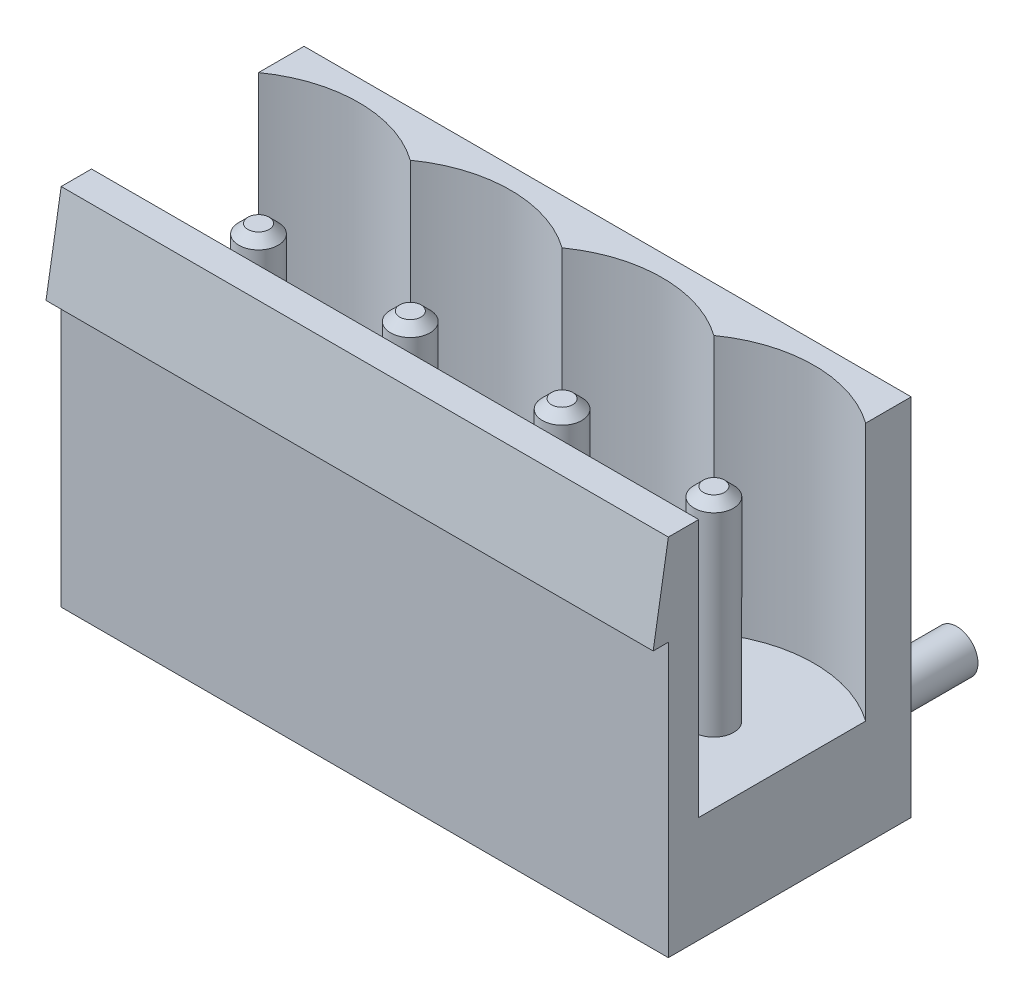
SolidWorks part; units mm, degrees
ref_plane "Спереди" through (0, 0, 0) normal (0, 0, 1) x (1, 0, 0)
ref_plane "Сверху" through (0, 0, 0) normal (0, 1, 0) x (1, 0, 0)
ref_plane "Справа" through (0, 0, 0) normal (1, 0, 0) x (0, 0, -1)
sketch "Эскиз1" plane through (0, 0, 0) normal (1, 0, 0) x (0, -1, 0)
  line L0 (-9, 0) -> (-9, -0.5)
  line L1 (0, 0) -> (-9, 0)
  line L2 (0, 0) -> (0, 8)
  line L3 (0, 8) -> (-12, 8)
  line L4 (-12, 0) -> (-12, 8)
  line L5 (-9, -0.5) -> (-12, 0)
  dimension "D1" = 12
  dimension "D2" = 8
  dimension "D3" = 3
  dimension "D4" = 0.5
extrude "Вытянуть1" add sketch "Эскиз1" along normal blind 20
ref_plane "Плоскость1" through (0.25, 0, 0) normal (1, 0, 0) x (0, 0, -1)
sketch "Эскиз5" plane through (0, 8, -8) normal (0, 0, 1) x (1, 0, 0)
  line L0 (20, -8) -> (0, -8) construction
  line L1 (0, -8) -> (0, 4) construction
  circle A0 centre (2.5, -6.5) radius 0.7
  dimension "D1" = 1.4
  dimension "D2" = 1.5
  dimension "D3" = 2.5
extrude "Вытянуть3" add sketch "Эскиз5" against normal blind 4
sketch "Эскиз6" plane through (0, 12, 0) normal (0, 1, 0) x (1, 0, 0)
  line L0 (2.5, 6.5) -> (2.5, 2.9937) construction
  line L1 (0, 6.5) -> (5, 6.5) construction
  line L2 (0, 6.5) -> (0, 1)
  line L3 (0, 1) -> (5, 1)
  line L4 (5, 6.5) -> (5, 1)
  line L5 (0, 8) -> (0, 0) construction
  line L6 (20, 0) -> (0, 0) construction
  line L7 (20, 8) -> (0, 8) construction
  arc A0 (5, 6.5) -> (0, 6.5) centre (2.5, 2.9937) ccw
  point P10 (2.5, 7.3)
  dimension "D1" = 5
  dimension "D2" = 1
  dimension "D3" = 0.7
  dimension "D4" = 1.5
extrude "Вырез-Вытянуть1" cut sketch "Эскиз6" against normal blind 8.5
sketch "Эскиз7" plane through (0, 3.5, 0) normal (0, 1, 0) x (1, 0, 0)
  line L0 (2.5, 1) -> (2.5, 4) construction
  line L1 (0, 1) -> (5, 1) construction
  line L2 (20, 4) -> (2.5, 4) construction
  line L3 (20, 8) -> (20, 0) construction
  circle A0 centre (2.5, 4) radius 0.65
  dimension "D1" = 1.3
extrude "Вытянуть4" add sketch "Эскиз7" along normal offset from surface (6.7 mm away) 1.8 up to face at (6.25, 12, -3.975)
chamfer "Фаска1" distance 0.3 angle 45 1 edges at (2.5, 10.2, -4.65)
pattern_linear "Линейный массив2" count 4 spacing 5 along (1, 0, 0) of "Вытянуть3", "Вырез-Вытянуть1"
sketch3d "Трехмерный эскиз1"
  point P0 (2.5, 29, -4.1779)
  point P1 (7.5, 29, -4.1779)
  point P2 (12.5, 29, -4.1779)
  point P3 (17.5, 29, -4.1779)
  point P4 (22.5, 29, -4.1779)
pattern_linear "Линейный массив3" count 4 spacing 5 along (1, 0, 0) of "Вытянуть4", "Фаска1"
sketch "Эскиз8" plane through (20, 0, 0) normal (1, 0, 0) x (0, 0, -1)
  line L0 (0, 12) -> (8, 12)
  line L1 (8, 12) -> (8, 0)
  line L2 (8, 0) -> (0, 0)
  line L3 (0, 0) -> (0, 9)
  line L4 (0, 9) -> (-0.5, 9)
  line L5 (-0.5, 9) -> (0, 12)
extrude "Вытянуть5" add sketch "Эскиз8" along normal blind 0.5
sketch "Эскиз9" plane through (0, 0, 0) normal (-1, 0, 0) x (0, 0, 1)
  line L0 (-8, 12) -> (0, 12)
  line L1 (0, 12) -> (0.5, 9)
  line L2 (0.5, 9) -> (0, 9)
  line L3 (0, 9) -> (0, 0)
  line L4 (0, 0) -> (-8, 0)
  line L5 (-8, 0) -> (-8, 12)
extrude "Вытянуть6" add sketch "Эскиз9" along normal blind 0.5
sketch "Эскиз10" plane through (0, 12, 0) normal (0, 1, 0) x (1, 0, 0)
  line L0 (20.5, -0.5) -> (-0.5, -0.5) construction
  line L1 (20.5, 8) -> (20, 8)
  line L2 (20.5, 8) -> (20.5, -0.5)
  line L3 (20.5, -0.5) -> (20, -0.5)
  line L4 (20, 8) -> (20, -0.5)
  line L5 (0, 6.5) -> (0, 1) construction
  line L6 (-0.5, 8) -> (0, 8)
  line L7 (-0.5, 8) -> (-0.5, -0.5)
  line L8 (-0.5, -0.5) -> (0, -0.5)
  line L9 (0, 8) -> (0, -0.5)
  line L10 (20, 1) -> (20, 6.5) construction
extrude "Вырез-Вытянуть2" cut sketch "Эскиз10" against normal up to next
